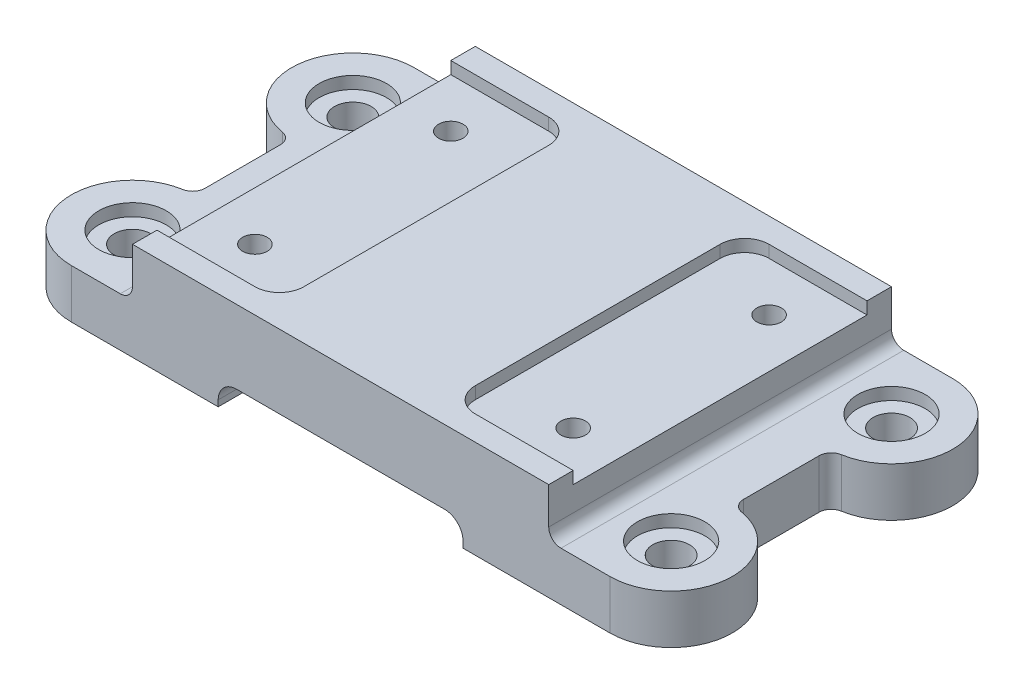
SolidWorks part; units mm, degrees
ref_plane "Front Plane" through (0, 0, 0) normal (0, 0, 1) x (1, 0, 0)
ref_plane "Top Plane" through (0, 0, 0) normal (0, 1, 0) x (1, 0, 0)
ref_plane "Right Plane" through (0, 0, 0) normal (1, 0, 0) x (0, 0, -1)
sketch "Sketch1" plane through (0, 0, 0) normal (0, 0, 1) x (1, 0, 0)
  line L1 (69.85, 25.4) -> (123.825, 25.4)
  line L3 (123.825, 25.4) -> (123.825, 15.875)
  line L4 (127, 12.7) -> (139.7, 12.7)
  line L5 (139.7, 12.7) -> (139.7, 0)
  line L7 (139.7, 0) -> (101.6, 0)
  line L9 (96.8248, 6.35) -> (69.85, 6.35)
  line L10 (139.7, 6.35) -> (117.475, 6.35) construction
  line L11 (139.7, 0) -> (117.475, 0) construction
  line L13 (101.6, 0) -> (101.6, 1.5748)
  line L14 (69.85, 25.4) -> (69.85, 6.35)
  arc A0 (101.6, 1.5748) -> (96.8248, 6.35) centre (96.8248, 1.5748) ccw
  arc A1 (123.825, 15.875) -> (127, 12.7) centre (127, 15.875) ccw
  dimension "D1" = 4.7752
  dimension "D2" = 3.175
extrude "Extrude1" add sketch "Sketch1" against normal blind 88.9
sketch "Sketch2" plane through (0, 0, 0) normal (0, 1, 0) x (1, 0, 0)
  line L1 (139.7, 57.15) -> (139.7, 88.9)
  line L2 (139.7, 0) -> (155.575, 0) construction
  line L3 (139.7, 15.875) -> (155.575, 15.875) construction
  line L4 (139.7, 44.45) -> (165.9353, 44.45) construction
  line L5 (139.7, 31.75) -> (139.7, 0)
  arc A0 (139.7, 0) -> (139.7, 31.75) centre (139.7, 15.875) ccw
  arc A1 (139.7, 88.9) -> (139.7, 57.15) centre (139.7, 73.025) cw
  dimension "D1" = 15.875
extrude "Extrude2" add sketch "Sketch2" along normal blind 12.7
ref_plane "Plane1" through (123.825, 25.4, 0) normal (0, 1, 0) x (-1, 0, 0)
sketch "Sketch3" plane through (123.825, 25.4, 0) normal (0, 1, 0) x (-1, 0, 0)
  line L0 (0, 0) -> (53.975, 0) construction
  line L1 (0, 0) -> (53.975, 0)
  line L2 (0, -88.9) -> (0, 0) construction
  line L3 (0, -82.55) -> (0, -6.35)
  line L4 (0, -88.9) -> (53.975, -88.9) construction
  line L5 (0, -88.9) -> (53.975, -88.9)
  line L6 (0, -6.35) -> (25.4, -6.35)
  line L7 (0, -82.55) -> (25.4, -82.55)
  line L8 (31.75, -76.2) -> (31.75, -12.7)
  line L9 (0, -6.35) -> (53.975, -6.35) construction
  line L10 (31.75, -88.9) -> (31.75, 0) construction
  line L11 (0, -82.55) -> (53.975, -82.55) construction
  line L12 (0, -88.9) -> (0, 0) construction
  arc A0 (25.4, -6.35) -> (31.75, -12.7) centre (25.4, -12.7) cw
  arc A1 (25.4, -82.55) -> (31.75, -76.2) centre (25.4, -76.2) ccw
  dimension "D4" = 6.35
  dimension "D1" = 6.35
  dimension "D2" = 6.35
  dimension "D3" = 31.75
extrude "Extrude3" cut sketch "Sketch3" against normal blind 3.175 contours L7 A1 L8 A0 L6 L3
hole_wizard "CBORE for 1/4 Binding Head Machine Screw1" positions "3DSketch1" profile "Sketch4" counterbore size "1/4" standard "Ansi Inch" end condition through all
sketch3d "3DSketch1"
  arc A0 (139.7, 12.7, -57.15) -> (139.7, 12.7, -88.9) centre (139.7, 12.7, -73.025) ccw construction
  arc A1 (139.7, 12.7, 0) -> (139.7, 12.7, -31.75) centre (139.7, 12.7, -15.875) ccw construction
  point P0 (139.7, 12.7, -73.025)
  point P2 (139.7, 12.7, -15.875)
  point P8 (139.7, 28.575, -73.025)
  point P12 (139.7, 28.575, -15.875)
sketch "Sketch4" plane through (139.7, 12.7, -73.025) normal (1, 0, 0) x (0, 0, 1)
  line L0 (0, 0) -> (0, 12.7)
  line L1 (0, 12.7) -> (4.7625, 12.7)
  line L3 (4.7625, 12.7) -> (4.7625, 3.175)
  line L4 (4.7625, 3.175) -> (8.7376, 3.175)
  line L5 (8.7376, 3.175) -> (8.7376, 0)
  line L7 (8.7376, 0) -> (0, 0)
  line L11 (0, -6.35) -> (0, 107.95) construction
  dimension "Thru Hole Dia." = 9.525
  dimension "Thru Hole Depth" = 12.7
  dimension "C'Bore Dia." = 17.4752
  dimension "C'Bore Depth" = 3.175
hole_wizard "1/4-20 Tapped Hole1" positions "3DSketch2" profile "Sketch5" tap size "1/4-20" standard "Ansi Inch"
sketch3d "3DSketch2"
  line L6 (123.825, 22.225, -82.55) -> (98.425, 22.225, -82.55) construction
  line L8 (92.075, 22.225, -76.2) -> (92.075, 22.225, -12.7) construction
  line L9 (123.825, 22.225, -6.35) -> (98.425, 22.225, -6.35) construction
  point P0 (111.125, 22.225, -19.05)
  point P2 (111.125, 22.225, -69.85)
  dimension "D1" = 19.05
  dimension "D4" = 19.05
  dimension "D2" = 12.7
  dimension "D3" = 12.7
sketch "Sketch5" plane through (111.125, 22.225, -19.05) normal (1, 0, 0) x (0, 0, 1)
  line L0 (0, 0) -> (0, 17.5358)
  line L1 (0, 17.5358) -> (2.5527, 16.002)
  line L2 (2.5527, 16.002) -> (2.5527, 12.7)
  line L3 (2.5527, 12.7) -> (3.175, 12.7)
  line L4 (3.175, 12.7) -> (3.175, 0)
  line L5 (3.175, 0) -> (0, 0)
  line L10 (0, 17.5358) -> (-2.5527, 16.002) construction
  line L11 (0, -6.35) -> (0, 107.95) construction
  dimension "Tap Drill Dia." = 5.1054
  dimension "Tap Drill Depth" = 16.002
  dimension "Thread Major Dia." = 6.35
  dimension "Thread Depth" = 12.7
  dimension "Drill Angle" = 118
fillet "Fillet2" radius 3.175 2 edges at (139.7, 6.35, -57.15) (139.7, 6.35, -31.75)
mirror "Mirror1" about plane through (69.85, 25.4, -88.9) normal (-1, 0, 0) of "Extrude1", "Extrude2", "Extrude3", "CBORE for 1/4 Binding Head Machine Screw1", "1/4-20 Tapped Hole1", "Fillet2"
